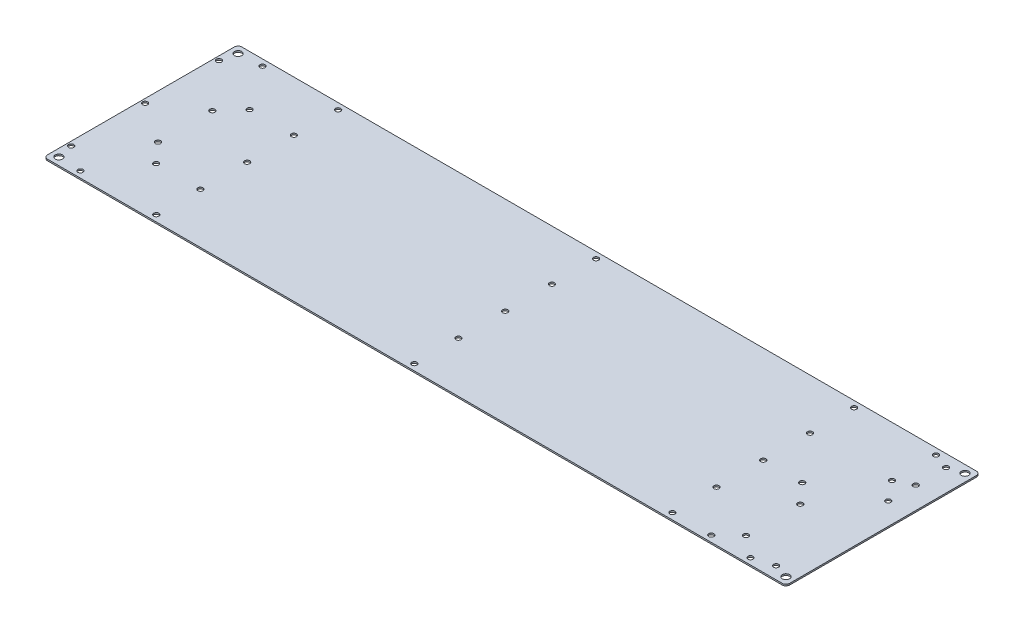
SolidWorks part; units mm, degrees
ref_plane "Front Plane" through (0, 0, 0) normal (0, 0, 1) x (1, 0, 0)
ref_plane "Top Plane" through (0, 0, 0) normal (0, 1, 0) x (1, 0, 0)
ref_plane "Right Plane" through (0, 0, 0) normal (1, 0, 0) x (0, 0, -1)
sketch "Sketch1" plane through (0, 0, 0) normal (0, 1, 0) x (1, 0, 0)
  line L1 (-244.475, 64) -> (244.475, 64)
  line L2 (-244.475, 64) -> (-244.475, -64)
  line L3 (-244.475, -64) -> (244.475, -64)
  line L4 (244.475, 64) -> (244.475, -64)
  line L5 (-244.475, 64) -> (244.475, -64) construction
  line L6 (-244.475, -64) -> (244.475, 64) construction
  point P0 (0, 0)
  dimension "D1" = 128
  dimension "D2" = 488.95
extrude "Boss-Extrude1" add sketch "Sketch1" along normal blind 1
fillet "Fillet1" radius 2.5 4 edges at (244.475, 0.5, -64) (244.475, 0.5, 64) (-244.475, 0.5, -64) (-244.475, 0.5, 64)
hole_wizard "M4 Clearance Hole1" positions "Sketch2" profile "Sketch3" hole size "M4" standard "ANSI Metric" end condition through all
sketch "Sketch2" plane through (0, 1, 0) normal (0, 1, 0) x (1, 0, 0)
  point P2 (239.475, -59)
  point P5 (239.475, 59)
  point P8 (-239.475, -59)
  point P11 (-239.475, 59)
  point P15 (0, 0)
sketch "Sketch3" plane through (239.475, 1, 59) normal (1, 0, 0) x (0, 0, 1)
  line L0 (0, 0) -> (0, 1)
  line L1 (0, 1) -> (2.4, 1)
  line L2 (2.4, 1) -> (2.4, 0)
  line L5 (2.4, 0) -> (0, 0)
  line L11 (0, -6.35) -> (0, 107.95) construction
  dimension "Thru Hole Dia." = 4.8
  dimension "Thru Hole Depth" = 1
hole_wizard "M3 Clearance Hole1" positions "Sketch4" profile "Sketch5" hole size "M3" standard "ANSI Metric" end condition through all
sketch "Sketch4" plane through (0, 1, 0) normal (0, 1, 0) x (1, 0, 0)
  point P0 (229.975, -56)
  point P3 (216.975, -59.85)
  point P6 (202.825, -48.7)
  point P9 (191.175, -59.85)
  point P12 (165.525, -59.85)
  point P15 (-4.475, -59.85)
  point P18 (-241.725, -48.7)
  point P21 (-224.475, -59.85)
  point P24 (-174.475, -59.85)
  point P27 (-241.725, 0)
  point P30 (-241.725, 48.7)
  point P33 (-203.675, -30.8)
  point P36 (-174.475, -30.8)
  point P39 (-215.325, -17.9)
  point P42 (-4.475, -30.8)
  point P45 (165.525, -30.8)
  point P48 (229.975, 56)
  point P51 (219.475, 59.85)
  point P54 (229.975, 36)
  point P57 (219.475, 30.8)
  point P60 (229.975, 17.9)
  point P63 (202.825, -12.9)
  point P66 (191.175, 0)
  point P69 (165.525, 0)
  point P72 (165.525, 30.8)
  point P75 (165.525, 59.85)
  point P78 (-4.475, 59.85)
  point P83 (-174.398, 59.85)
  point P87 (-224.233, 59.85)
  point P89 (-174.475, 30.8)
  point P92 (-174.475, 0)
  point P95 (-215.325, 17.9)
  point P98 (-203.675, 30.8)
  point P101 (-4.475, 30.8)
  point P104 (-4.475, 0)
sketch "Sketch5" plane through (229.975, 1, 56) normal (1, 0, 0) x (0, 0, 1)
  line L0 (0, 0) -> (0, 1)
  line L1 (0, 1) -> (1.7, 1)
  line L2 (1.7, 1) -> (1.7, 0)
  line L5 (1.7, 0) -> (0, 0)
  line L11 (0, -6.35) -> (0, 107.95) construction
  dimension "Thru Hole Dia." = 3.4
  dimension "Thru Hole Depth" = 1
